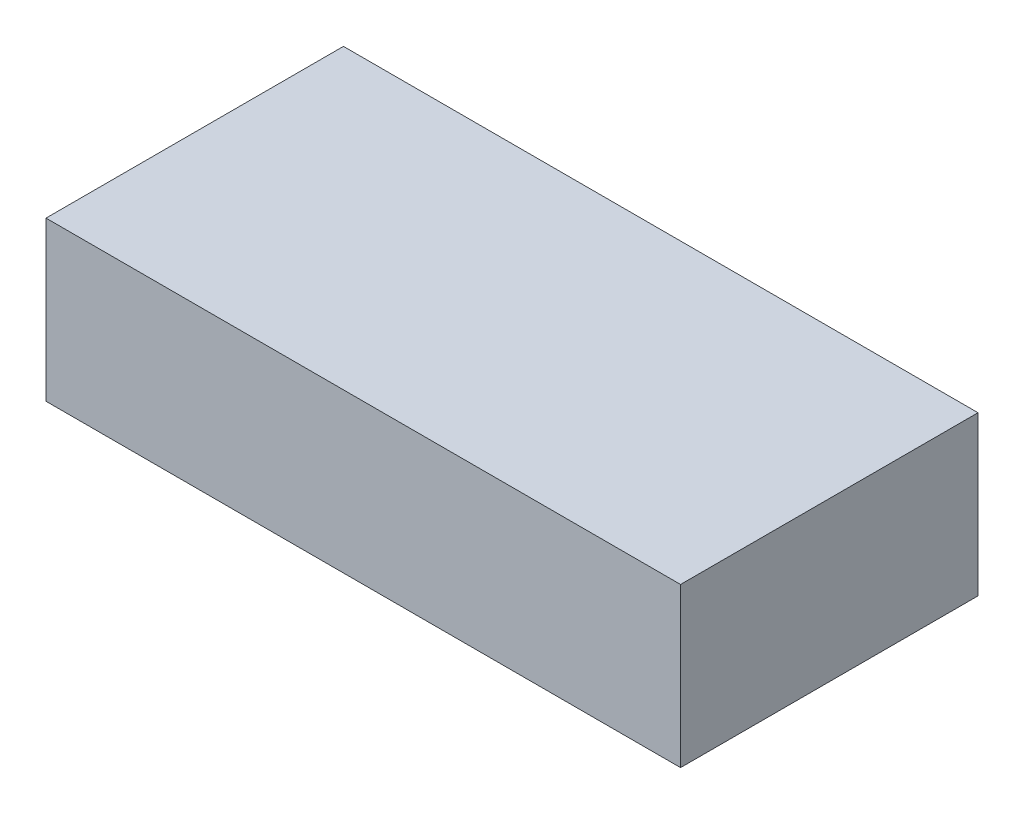
SolidWorks part; units mm, degrees
material "PET"
ref_plane "Front Plane" through (0, 0, 0) normal (0, 0, 1) x (1, 0, 0)
ref_plane "Top Plane" through (0, 0, 0) normal (0, 1, 0) x (1, 0, 0)
ref_plane "Right Plane" through (0, 0, 0) normal (1, 0, 0) x (0, 0, -1)
sketch "Sketch1" plane through (0, 0, 0) normal (0, 1, 0) x (1, 0, 0)
  line L1 (-16, -7.5) -> (16, -7.5)
  line L2 (-16, -7.5) -> (-16, 7.5)
  line L3 (-16, 7.5) -> (16, 7.5)
  line L4 (16, -7.5) -> (16, 7.5)
  line L5 (-16, -7.5) -> (16, 7.5) construction
  line L6 (-16, 7.5) -> (16, -7.5) construction
  point P0 (0, 0)
  dimension "D1" = 32
  dimension "D2" = 15
extrude "Boss-Extrude1" add sketch "Sketch1" along normal mid plane 8
